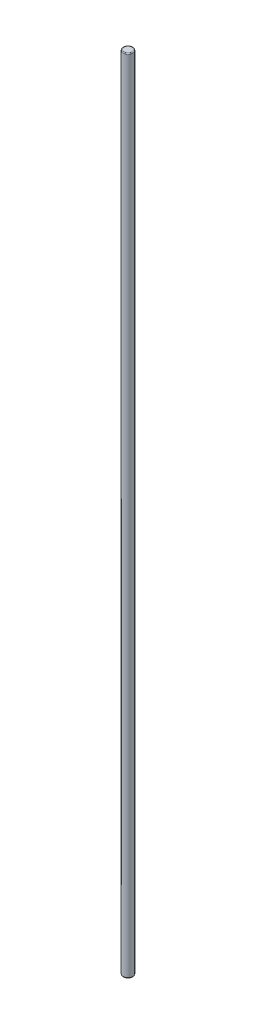
SolidWorks part; units mm, degrees
ref_plane "Front Plane" through (0, 0, 0) normal (0, 0, 1) x (1, 0, 0)
ref_plane "Top Plane" through (0, 0, 0) normal (0, 1, 0) x (1, 0, 0)
ref_plane "Right Plane" through (0, 0, 0) normal (1, 0, 0) x (0, 0, -1)
sketch "Sketch1" plane through (0, 0, 0) normal (0, 1, 0) x (1, 0, 0)
  circle A0 centre (0, 0) radius 6
  dimension "D1" = 12
extrude "Boss-Extrude1" add sketch "Sketch1" along normal blind 1000
fillet "Fillet1" radius 1 2 edges at (0, 0, 6) (0, 1000, 6)
